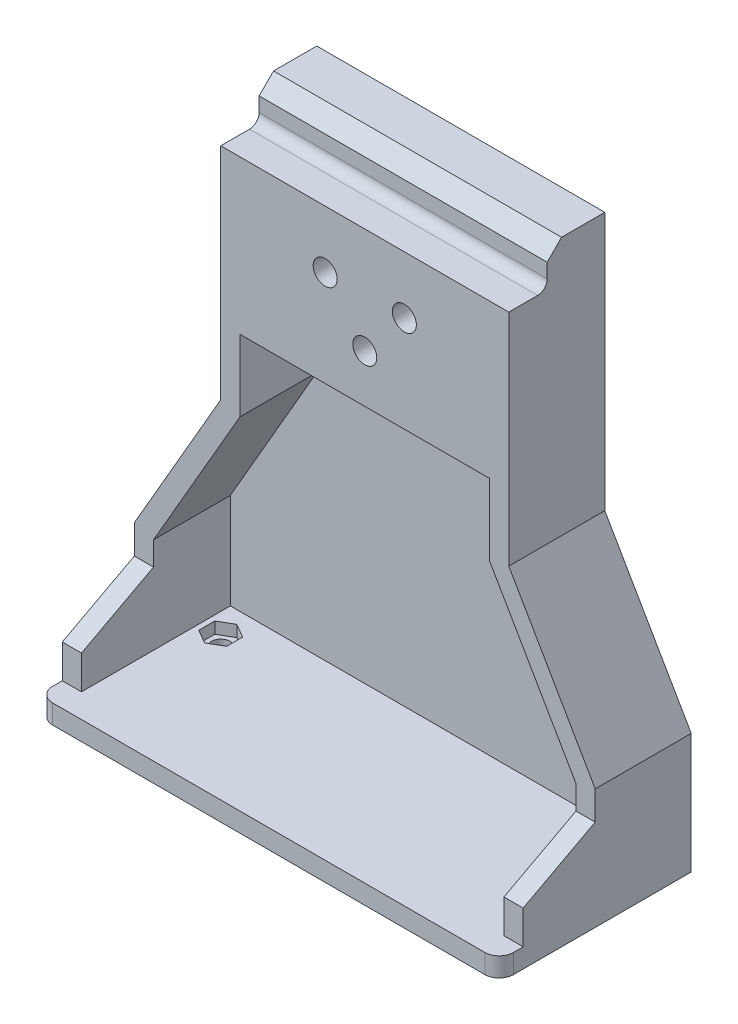
SolidWorks part; units mm, degrees
ref_plane "前视基准面" through (0, 0, 0) normal (0, 0, 1) x (1, 0, 0)
ref_plane "上视基准面" through (0, 0, 0) normal (0, 1, 0) x (1, 0, 0)
ref_plane "右视基准面" through (0, 0, 0) normal (1, 0, 0) x (0, 0, -1)
other "Configuration Table"
sketch "草图1" plane through (0, 0, 0) normal (0, 0, 1) x (1, 0, 0)
  line L1 (-48, -55) -> (48, -55)
  line L2 (-48, -55) -> (-48, 55)
  line L3 (-48, 55) -> (48, 55)
  line L4 (48, -55) -> (48, 55)
  line L5 (-48, -55) -> (48, 55) construction
  line L6 (-48, 55) -> (48, -55) construction
  point P0 (0, 0)
  dimension "D1" = 110
  dimension "D2" = 96
extrude "凸台-拉伸1" add sketch "草图1" along normal blind 20
sketch "草图2" plane through (0, 0, 20) normal (0, 0, 1) x (1, 0, 0)
  line L0 (-48, -30) -> (-30, 1.1769)
  line L1 (-30, 1.1769) -> (-30, 55)
  line L2 (0, 0) -> (0, -55) construction
  line L3 (-48, -55) -> (48, -55) construction
  line L4 (48, -55) -> (48, 55)
  line L5 (48, 55) -> (-48, 55)
  line L6 (-48, 55) -> (-48, -55)
  line L7 (-48, -55) -> (48, -55)
  line L9 (-30, 55) -> (-48, 55)
  line L10 (-48, 55) -> (-48, -30)
  line L12 (48, 55) -> (48, -30)
  line L13 (30, 55) -> (48, 55)
  line L14 (30, 1.1769) -> (30, 55)
  line L15 (48, -30) -> (30, 1.1769)
  dimension "D2" = 25
  dimension "D3" = 30
  dimension "D4" = 60
  dimension "D1" = 0
extrude "切除-拉伸1" cut sketch "草图2" against normal blind 20
shell "抽壳1" thickness 4
sketch "草图3" plane through (0, -55, 0) normal (0, -1, 0) x (1, 0, 0)
  line L0 (0, 0) -> (0, 20) construction
  line L1 (-48, 20) -> (48, 20) construction
  line L2 (-40, 10) -> (40, 10) construction
  circle A0 centre (-40, 10) radius 2
  circle A1 centre (40, 10) radius 2
  point P7 (0, 10)
  point P8 (0, 10)
  dimension "D2" = 4
  dimension "D1" = 80
extrude "切除-拉伸2" cut sketch "草图3" against normal up to next
sketch "草图5" plane through (0, 0, 20) normal (0, 0, 1) x (1, 0, 0)
  line L0 (0, 0) -> (0, 25) construction
  line L1 (0, 25) -> (-8.25, 35.0468) construction
  line L3 (30, 55) -> (-30, 55) construction
  circle A0 centre (0, 25) radius 2.5
  circle A1 centre (-8.25, 35.0468) radius 2.5
  circle A2 centre (8.25, 35.0468) radius 2.5
  dimension "D1" = 13
  dimension "D4" = 5
  dimension "D5" = 13
  dimension "D2" = 16.5
  dimension "D3" = 30
extrude "切除-拉伸3" cut sketch "草图5" against normal up to next
sketch "草图6" plane through (0, -55, 0) normal (0, -1, 0) x (1, 0, 0)
  line L0 (0, 0) -> (0, 30) construction
  line L2 (-48, 40) -> (48, 40)
  line L3 (-48, 40) -> (-48, 20)
  line L4 (-48, 20) -> (48, 20)
  line L5 (48, 40) -> (48, 20)
  line L6 (-48, 40) -> (48, 20) construction
  line L7 (-48, 20) -> (48, 40) construction
  dimension "D1" = 20
extrude "凸台-拉伸2" add sketch "草图6" against normal up to surface (4 mm away) up to face at (-40, -51, 12)
sketch "草图7" plane through (-48, 0, 0) normal (-1, 0, 0) x (0, 0, 1)
  line L0 (20, -36) -> (35, -44)
  line L1 (20, -30) -> (20, -51) construction
  line L2 (35, -44) -> (35, -51)
  line L3 (40, -51) -> (20, -51) construction
  line L4 (35, -51) -> (20, -51)
  line L5 (20, -51) -> (20, -36)
  dimension "D1" = 15
  dimension "D2" = 7
  dimension "D3" = 15
extrude "凸台-拉伸3" add sketch "草图7" against normal blind 4
mirror "镜向1" about plane through (0, 0, 0) normal (1, 0, 0) of "凸台-拉伸3"
fillet "圆角1" radius 3 2 edges at (48, -53, 40) (-48, -53, 40)
sketch "草图8" plane through (0, -51, 0) normal (0, 1, 0) x (1, 0, 0)
  line L0 (0, 0) -> (0, -46.0888) construction
  line L1 (40, -13.3486) -> (42.9, -11.6743)
  line L2 (42.9, -11.6743) -> (42.9, -8.3257)
  line L3 (42.9, -8.3257) -> (40, -6.6514)
  line L4 (40, -6.6514) -> (37.1, -8.3257)
  line L5 (37.1, -8.3257) -> (37.1, -11.6743)
  line L6 (37.1, -11.6743) -> (40, -13.3486)
  line L7 (-37.1, -11.6743) -> (-40, -13.3486)
  line L8 (-37.1, -8.3257) -> (-37.1, -11.6743)
  line L9 (-40, -6.6514) -> (-37.1, -8.3257)
  line L10 (-42.9, -8.3257) -> (-40, -6.6514)
  line L11 (-42.9, -11.6743) -> (-42.9, -8.3257)
  line L12 (-40, -13.3486) -> (-42.9, -11.6743)
  circle A0 centre (40, -10) radius 2.9 construction
  circle A1 centre (-40, -10) radius 2.9 construction
  dimension "D1" = 5.8
extrude "切除-拉伸4" cut sketch "草图8" against normal blind 2.4
sketch "草图10" plane through (-30, 0, 0) normal (-1, 0, 0) x (0, 0, 1)
  line L1 (12, 47) -> (20, 47)
  line L2 (12, 47) -> (12, 55)
  line L3 (12, 55) -> (20, 55)
  line L4 (20, 47) -> (20, 55)
  line L5 (12, 47) -> (20, 55) construction
  line L6 (12, 55) -> (20, 47) construction
  point P0 (16, 51)
  dimension "D1" = 8
  dimension "D2" = 8
extrude "切除-拉伸5" cut sketch "草图10" against normal through all
sketch "草图11" plane through (0, 0, 20) normal (0, 0, 1) x (1, 0, 0)
  line L0 (0, 55) -> (0, 22.1) construction
  line L1 (30, 55) -> (-30, 55) construction
  line L2 (-15, 37.1) -> (-15, 55) construction
  line L3 (-15, 55) -> (15, 55) construction
  line L4 (15, 37.1) -> (15, 55) construction
  line L5 (-16, 37.1) -> (-16, 56)
  line L6 (-16, 56) -> (16, 56)
  line L7 (16, 37.1) -> (16, 56)
  arc A0 (-15, 37.1) -> (15, 37.1) centre (0, 37.1) ccw construction
  arc A1 (-16, 37.1) -> (16, 37.1) centre (0, 37.1) ccw
  dimension "D2" = 30
  dimension "D1" = 32.9
  dimension "D3" = 1
fillet "圆角2" radius 2 1 edges at (0, 47, 12)
chamfer "倒角1" distance 3 angle 45 1 edges at (0, 55, 12)
